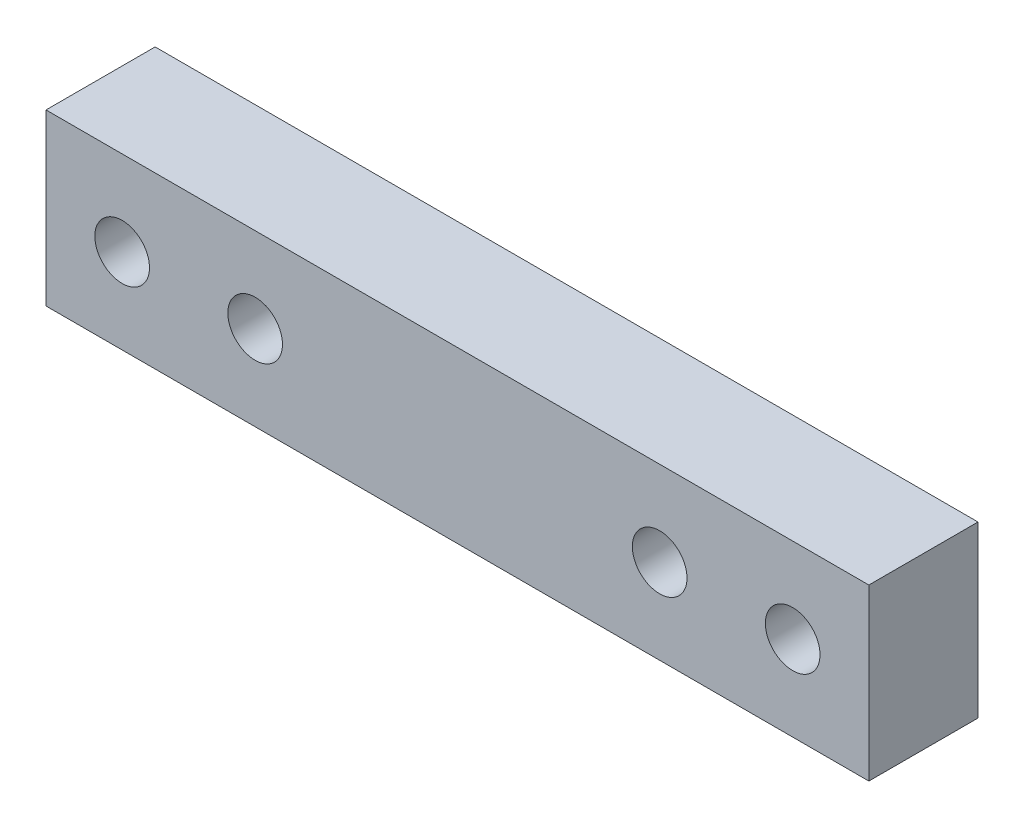
SolidWorks part; units mm, degrees
ref_plane "Alzado" through (0, 0, 0) normal (0, 0, 1) x (1, 0, 0)
ref_plane "Planta" through (0, 0, 0) normal (0, 1, 0) x (1, 0, 0)
ref_plane "Vista lateral" through (0, 0, 0) normal (1, 0, 0) x (0, 0, -1)
sketch "Croquis1" plane through (0, 0, 0) normal (0, 0, 1) x (1, 0, 0)
  line L0 (0, 4.66) -> (45.16, 4.66) construction
  line L1 (0, 0) -> (45.16, 0)
  line L2 (0, 0) -> (0, 9.32)
  line L3 (0, 9.32) -> (45.16, 9.32)
  line L4 (45.16, 0) -> (45.16, 9.32)
  line L5 (22.58, 0) -> (22.58, 9.32) construction
  circle A0 centre (4.18, 4.66) radius 1.5
  circle A1 centre (11.48, 4.66) radius 1.5
  circle A2 centre (40.98, 4.66) radius 1.5
  circle A3 centre (33.68, 4.66) radius 1.5
  dimension "D5" = 3
  dimension "D1" = 45.16
  dimension "D2" = 9.32
  dimension "D3" = 4.18
  dimension "D4" = 7.3
extrude "Saliente-Extruir1" add sketch "Croquis1" along normal blind 5.99
